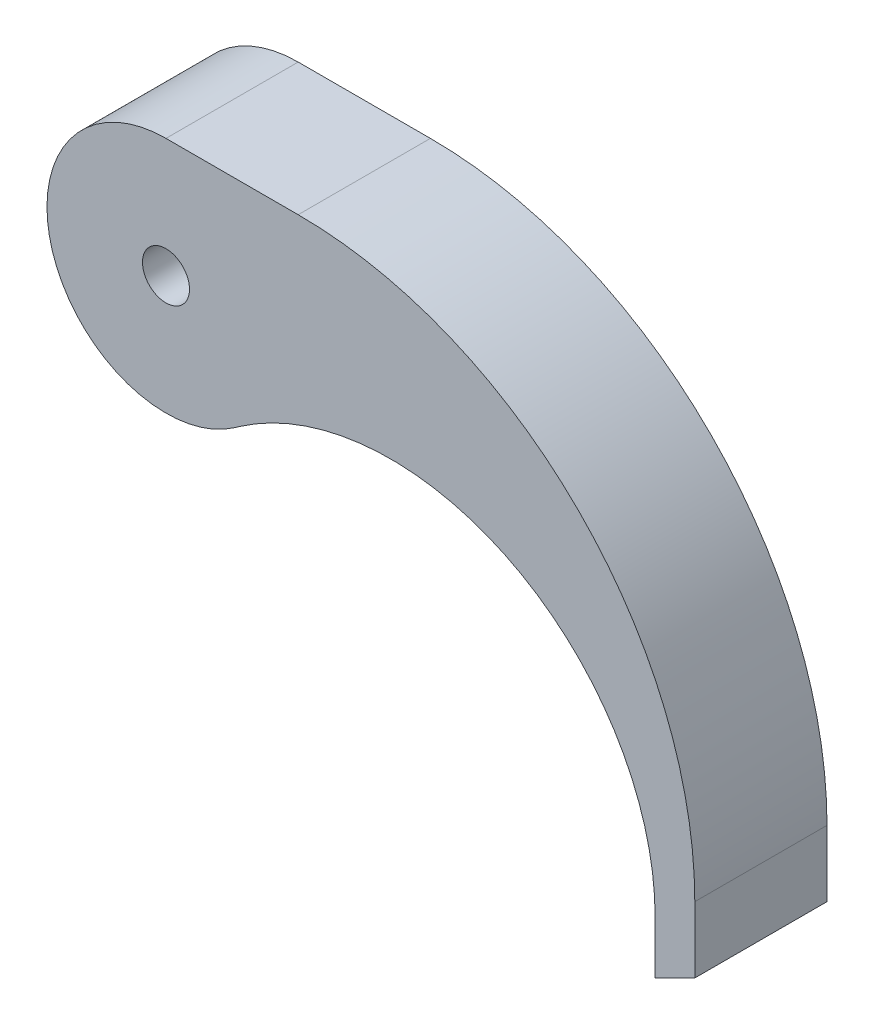
SolidWorks part; units mm, degrees
ref_plane "Front Plane" through (0, 0, 0) normal (0, 0, 1) x (1, 0, 0)
ref_plane "Top Plane" through (0, 0, 0) normal (0, 1, 0) x (1, 0, 0)
ref_plane "Right Plane" through (0, 0, 0) normal (1, 0, 0) x (0, 0, -1)
sketch "Sketch1" plane through (0, 0, 0) normal (0, 0, 1) x (1, 0, 0)
  line L0 (0, 9) -> (10, 9)
  line L1 (40, -21) -> (40, -26)
  line L2 (5.1486, -7.3819) -> (5.5587, -7.0958)
  line L3 (37, -27.5) -> (37, -23.5)
  line L4 (40, -26) -> (37, -27.5)
  circle A0 centre (0, 0) radius 1.778
  arc A2 (10, 9) -> (40, -21) centre (10, -21) cw
  arc A3 (5.5587, -7.0958) -> (37, -23.5) centre (17, -23.5) cw
  arc A4 (0, 9) -> (5.1486, -7.3819) centre (0, 0) ccw
  dimension "D1" = 9
  dimension "D2" = 3
  dimension "D3" = 30
  dimension "D6" = 20
  dimension "D8" = 0.5
  dimension "D9" = 3.556
  dimension "D4" = 5
  dimension "D5" = 10
  dimension "D7" = 4
extrude "Boss-Extrude1" add sketch "Sketch1" along normal blind 10
